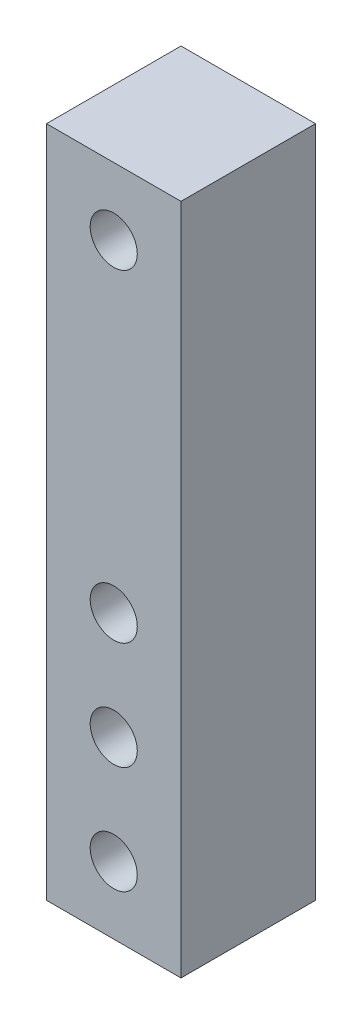
SolidWorks part; units mm, degrees
ref_plane "正面" through (0, 0, 0) normal (0, 0, 1) x (1, 0, 0)
ref_plane "平面" through (0, 0, 0) normal (0, 1, 0) x (1, 0, 0)
ref_plane "右側面" through (0, 0, 0) normal (1, 0, 0) x (0, 0, -1)
sketch "ｽｹｯﾁ1" plane through (0, 0, 0) normal (0, 0, 1) x (1, 0, 0)
  line L0 (0, 25) -> (0, -25) construction
  line L1 (-5, 25) -> (5, 25)
  line L2 (-5, 25) -> (-5, -25)
  line L3 (-5, -25) -> (5, -25)
  line L4 (5, 25) -> (5, -25)
  line L5 (-5, 25) -> (5, -25) construction
  line L6 (-5, -25) -> (5, 25) construction
  circle A0 centre (0, -20) radius 1.75
  circle A1 centre (0, -12) radius 1.75
  circle A2 centre (0, -4) radius 1.75
  circle A3 centre (0, 20) radius 1.75
  point P0 (0, 0)
  dimension "D3" = 3.5
  dimension "D4" = 3.5
  dimension "D5" = 3.5
  dimension "D6" = 5
  dimension "D7" = 8
  dimension "D8" = 8
  dimension "D9" = 3.5
  dimension "D1" = 10
  dimension "D2" = 50
  dimension "D10" = 5
extrude "ﾎﾞｽ - 押し出し1" add sketch "ｽｹｯﾁ1" along normal blind 10
